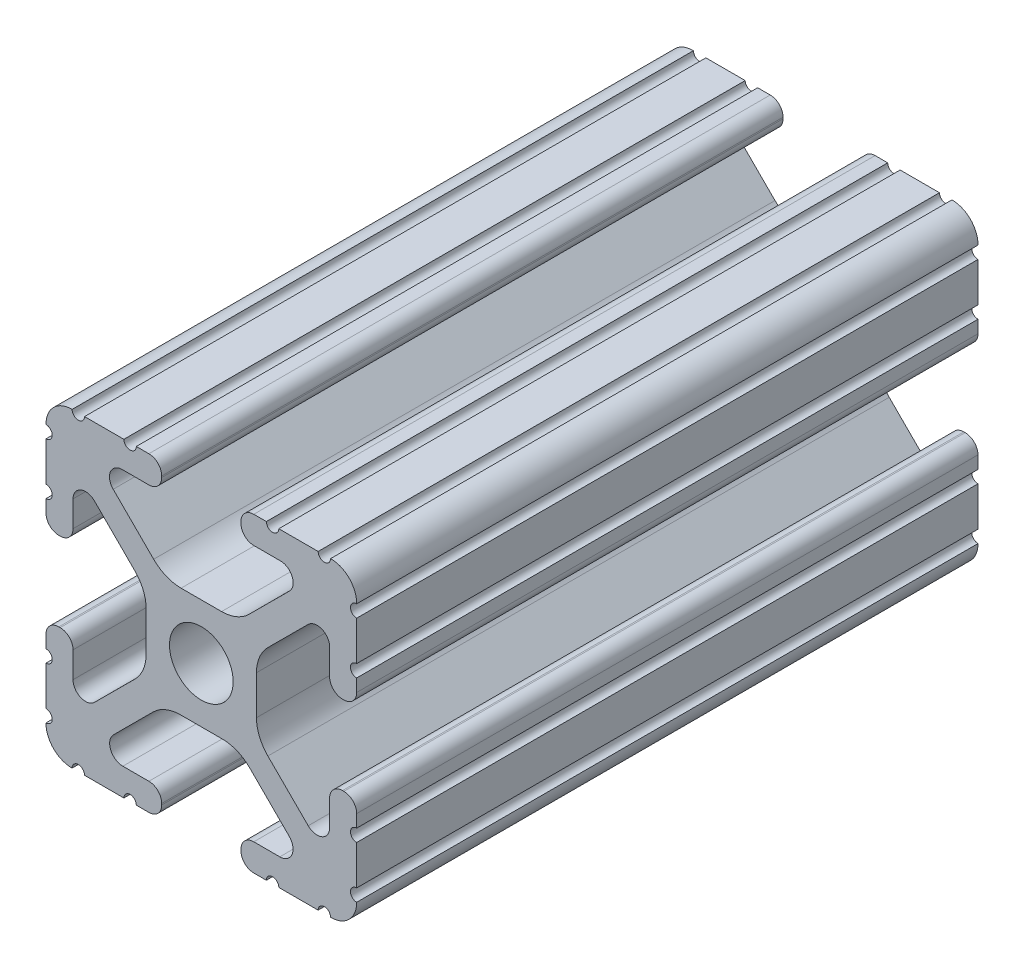
SolidWorks part; units mm, degrees
ref_plane "Front Plane" through (0, 0, 0) normal (0, 0, 1) x (1, 0, 0)
ref_plane "Top Plane" through (0, 0, 0) normal (0, 1, 0) x (1, 0, 0)
ref_plane "Right Plane" through (0, 0, 0) normal (1, 0, 0) x (0, 0, -1)
sketch "Sketch1" plane through (0, 0, 0) normal (0, 0, 1) x (1, 0, 0)
  line L0 (-7.207, 8.7244) -> (-3.8983, 5.4232)
  line L1 (-4.2875, 10.4902) -> (-6.4768, 10.4902)
  line L2 (-3.2385, 11.651) -> (-3.2385, 11.5392)
  line L3 (-5.3171, 12.7) -> (-4.2875, 12.7)
  line L4 (0, 13.4005) -> (0, -14.8534) construction
  line L5 (12.7, 0) -> (-13.9989, 0) construction
  line L6 (-9.5504, 12.7) -> (-6.3331, 12.7)
  line L7 (-12.7, 6.3331) -> (-12.7, 9.5504)
  line L8 (-12.7, 4.2875) -> (-12.7, 5.3171)
  line L9 (-11.5392, 3.2385) -> (-11.651, 3.2385)
  line L10 (-10.4902, 6.4021) -> (-10.4902, 4.2875)
  line L11 (-5.441, 3.8408) -> (-8.7371, 7.1294)
  line L12 (-4.5085, -1.5932) -> (-4.5085, 1.5932)
  line L13 (-1.7093, -4.4958) -> (1.7093, -4.4958)
  line L14 (3.9523, -5.4237) -> (7.1797, -8.6452)
  line L15 (6.4164, -10.4902) -> (4.2875, -10.4902)
  line L16 (3.2385, -11.5392) -> (3.2385, -11.651)
  line L17 (4.2875, -12.7) -> (5.3171, -12.7)
  line L18 (6.3331, -12.7) -> (9.5504, -12.7)
  line L19 (12.7, -9.5504) -> (12.7, -6.3331)
  line L20 (12.7, -5.3171) -> (12.7, -4.2875)
  line L21 (11.651, -3.2385) -> (11.5392, -3.2385)
  line L22 (10.4902, -4.2875) -> (10.4902, -6.4021)
  line L23 (8.7371, -7.1294) -> (5.441, -3.8408)
  line L24 (4.5085, -1.5932) -> (4.5085, 1.5932)
  line L25 (5.441, 3.8408) -> (8.7371, 7.1294)
  line L26 (10.4902, 6.4021) -> (10.4902, 4.2875)
  line L27 (11.5392, 3.2385) -> (11.651, 3.2385)
  line L28 (12.7, 4.2875) -> (12.7, 5.3171)
  line L29 (12.7, 6.3331) -> (12.7, 9.5504)
  line L30 (9.5504, 12.7) -> (6.3331, 12.7)
  line L31 (5.3171, 12.7) -> (4.2875, 12.7)
  line L32 (3.2385, 11.651) -> (3.2385, 11.5392)
  line L33 (4.2875, 10.4902) -> (6.4768, 10.4902)
  line L34 (7.207, 8.7244) -> (3.8983, 5.4232)
  line L35 (1.6558, 4.4958) -> (-1.6558, 4.4958)
  line L36 (-8.7371, -7.1294) -> (-5.441, -3.8408)
  line L37 (-10.4902, -4.2875) -> (-10.4902, -6.4021)
  line L38 (-11.651, -3.2385) -> (-11.5392, -3.2385)
  line L39 (-12.7, -5.3171) -> (-12.7, -4.2875)
  line L40 (-12.7, -9.5504) -> (-12.7, -6.3331)
  line L41 (-6.3331, -12.7) -> (-9.5504, -12.7)
  line L42 (-4.2875, -12.7) -> (-5.3171, -12.7)
  line L43 (-3.2385, -11.5392) -> (-3.2385, -11.651)
  line L44 (-6.4164, -10.4902) -> (-4.2875, -10.4902)
  line L45 (-3.9523, -5.4237) -> (-7.1797, -8.6452)
  arc A0 (-7.207, 8.7244) -> (-6.4768, 10.4902) centre (-6.4768, 9.4563) cw
  arc A1 (-3.2385, 11.5392) -> (-4.2875, 10.4902) centre (-4.2875, 11.5392) cw
  arc A2 (-4.2875, 12.7) -> (-3.2385, 11.651) centre (-4.2875, 11.651) cw
  arc A3 (-5.3171, 12.7) -> (-6.3331, 12.7) centre (-5.8251, 12.7) cw
  arc A4 (-9.5504, 12.7) -> (-10.5664, 12.6998) centre (-10.0584, 12.7) cw
  arc A5 (-12.6998, 10.5664) -> (-10.5664, 12.6998) centre (-10.5918, 10.5918) cw
  arc A6 (-12.6998, 10.5664) -> (-12.7, 9.5504) centre (-12.7, 10.0584) cw
  arc A7 (-12.7, 6.3331) -> (-12.7, 5.3171) centre (-12.7, 5.8251) cw
  arc A8 (-11.651, 3.2385) -> (-12.7, 4.2875) centre (-11.651, 4.2875) cw
  arc A9 (-10.4902, 4.2875) -> (-11.5392, 3.2385) centre (-11.5392, 4.2875) cw
  circle A10 centre (0, 0) radius 2.6035
  arc A11 (-10.4902, 6.4021) -> (-8.7371, 7.1294) centre (-9.4628, 6.4021) cw
  arc A12 (-5.441, 3.8408) -> (-4.5085, 1.5932) centre (-7.6835, 1.5932) cw
  arc A13 (-4.5085, -1.5932) -> (-5.441, -3.8408) centre (-7.6835, -1.5932) cw
  arc A14 (-8.7371, -7.1294) -> (-10.4902, -6.4021) centre (-9.4628, -6.4021) cw
  arc A15 (-1.7093, -4.4958) -> (-3.9523, -5.4237) centre (-1.7093, -7.6708) ccw
  arc A16 (3.9523, -5.4237) -> (1.7093, -4.4958) centre (1.7093, -7.6708) ccw
  arc A17 (6.4164, -10.4902) -> (7.1797, -8.6452) centre (6.4164, -9.4098) ccw
  arc A18 (4.2875, -10.4902) -> (3.2385, -11.5392) centre (4.2875, -11.5392) ccw
  arc A19 (3.2385, -11.651) -> (4.2875, -12.7) centre (4.2875, -11.651) ccw
  arc A20 (6.3331, -12.7) -> (5.3171, -12.7) centre (5.8251, -12.7) ccw
  arc A21 (10.5664, -12.6998) -> (9.5504, -12.7) centre (10.0584, -12.7) ccw
  arc A22 (10.5664, -12.6998) -> (12.6998, -10.5664) centre (10.5918, -10.5918) ccw
  arc A23 (12.7, -9.5504) -> (12.6998, -10.5664) centre (12.7, -10.0584) ccw
  arc A24 (12.7, -5.3171) -> (12.7, -6.3331) centre (12.7, -5.8251) ccw
  arc A25 (12.7, -4.2875) -> (11.651, -3.2385) centre (11.651, -4.2875) ccw
  arc A26 (11.5392, -3.2385) -> (10.4902, -4.2875) centre (11.5392, -4.2875) ccw
  arc A27 (8.7371, -7.1294) -> (10.4902, -6.4021) centre (9.4628, -6.4021) ccw
  arc A28 (4.5085, -1.5932) -> (5.441, -3.8408) centre (7.6835, -1.5932) ccw
  arc A29 (5.441, 3.8408) -> (4.5085, 1.5932) centre (7.6835, 1.5932) ccw
  arc A30 (10.4902, 6.4021) -> (8.7371, 7.1294) centre (9.4628, 6.4021) ccw
  arc A31 (10.4902, 4.2875) -> (11.5392, 3.2385) centre (11.5392, 4.2875) ccw
  arc A32 (11.651, 3.2385) -> (12.7, 4.2875) centre (11.651, 4.2875) ccw
  arc A33 (12.7, 6.3331) -> (12.7, 5.3171) centre (12.7, 5.8251) ccw
  arc A34 (12.6998, 10.5664) -> (12.7, 9.5504) centre (12.7, 10.0584) ccw
  arc A35 (12.6998, 10.5664) -> (10.5664, 12.6998) centre (10.5918, 10.5918) ccw
  arc A36 (9.5504, 12.7) -> (10.5664, 12.6998) centre (10.0584, 12.7) ccw
  arc A37 (5.3171, 12.7) -> (6.3331, 12.7) centre (5.8251, 12.7) ccw
  arc A38 (4.2875, 12.7) -> (3.2385, 11.651) centre (4.2875, 11.651) ccw
  arc A39 (3.2385, 11.5392) -> (4.2875, 10.4902) centre (4.2875, 11.5392) ccw
  arc A40 (7.207, 8.7244) -> (6.4768, 10.4902) centre (6.4768, 9.4563) ccw
  arc A41 (1.6558, 4.4958) -> (3.8983, 5.4232) centre (1.6558, 7.6708) ccw
  arc A42 (-1.6558, 4.4958) -> (-3.8983, 5.4232) centre (-1.6558, 7.6708) cw
  arc A43 (-11.5392, -3.2385) -> (-10.4902, -4.2875) centre (-11.5392, -4.2875) cw
  arc A44 (-12.7, -4.2875) -> (-11.651, -3.2385) centre (-11.651, -4.2875) cw
  arc A45 (-12.7, -5.3171) -> (-12.7, -6.3331) centre (-12.7, -5.8251) cw
  arc A46 (-12.7, -9.5504) -> (-12.6998, -10.5664) centre (-12.7, -10.0584) cw
  arc A47 (-10.5664, -12.6998) -> (-12.6998, -10.5664) centre (-10.5918, -10.5918) cw
  arc A48 (-10.5664, -12.6998) -> (-9.5504, -12.7) centre (-10.0584, -12.7) cw
  arc A49 (-6.3331, -12.7) -> (-5.3171, -12.7) centre (-5.8251, -12.7) cw
  arc A50 (-3.2385, -11.651) -> (-4.2875, -12.7) centre (-4.2875, -11.651) cw
  arc A51 (-4.2875, -10.4902) -> (-3.2385, -11.5392) centre (-4.2875, -11.5392) cw
  arc A52 (-6.4164, -10.4902) -> (-7.1797, -8.6452) centre (-6.4164, -9.4098) cw
  dimension "D1" = 5.207
  dimension "D9" = 14.859
  dimension "D2" = 25.4
  dimension "D3" = 12.7
  dimension "D4" = 6.477
  dimension "D5" = 8.2042
  dimension "D6" = 9.017
  dimension "D8" = 2.2098
  dimension "D10" = 2.2098
extrude "Extrude1" add sketch "Sketch1" against normal blind 50.8
